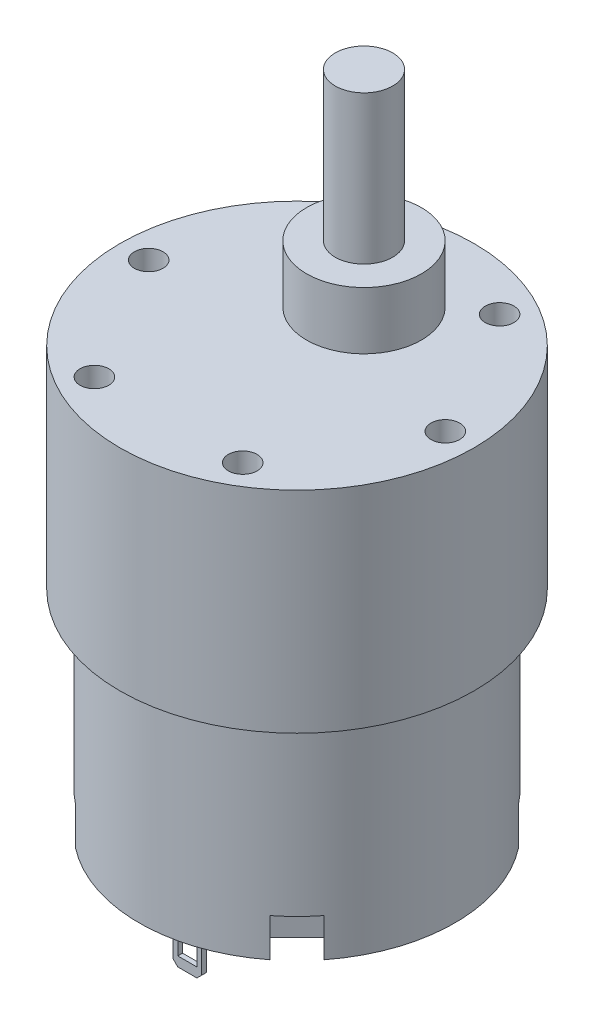
SolidWorks part; units mm, degrees
ref_plane "前视基准面" through (0, 0, 0) normal (0, 0, 1) x (1, 0, 0)
ref_plane "上视基准面" through (0, 0, 0) normal (0, 1, 0) x (1, 0, 0)
ref_plane "右视基准面" through (0, 0, 0) normal (1, 0, 0) x (0, 0, -1)
sketch "草图1" plane through (0, 0, 0) normal (0, 1, 0) x (1, 0, 0)
  circle A0 centre (0, 0) radius 16.5
extrude "凸台-拉伸1" add sketch "草图1" along normal blind 22
sketch "草图2" plane through (0, 22, 0) normal (0, 1, 0) x (1, 0, 0)
  circle A0 centre (0, 0) radius 18.5
extrude "凸台-拉伸2" add sketch "草图2" along normal blind 22
sketch "草图3" plane through (0, 44, 0) normal (0, 1, 0) x (1, 0, 0)
  circle A0 centre (0, 7) radius 6
extrude "凸台-拉伸3" add sketch "草图3" along normal blind 6
sketch "草图4" plane through (0, 50, 0) normal (0, 1, 0) x (1, 0, 0)
  circle A0 centre (0, 7) radius 3
extrude "凸台-拉伸7" add sketch "草图4" along normal blind 15.5
sketch "草图5" plane through (0, 0, 0) normal (0, -1, 0) x (1, 0, 0)
  line L0 (-10.9602, 8.1317) -> (-8.1317, 10.9602)
  line L1 (8.1317, 10.9602) -> (10.9602, 8.1317)
  line L2 (8.1317, 10.9602) -> (10.167, 12.9954)
  line L3 (-10.9602, 8.1317) -> (-12.9954, 10.167)
  line L4 (-8.1317, 10.9602) -> (-10.167, 12.9954)
  line L5 (10.9602, 8.1317) -> (12.9954, 10.167)
  line L6 (10.9602, -8.1317) -> (8.1317, -10.9602)
  line L7 (10.9602, -8.1317) -> (12.9954, -10.167)
  line L8 (8.1317, -10.9602) -> (10.167, -12.9954)
  line L9 (-8.1317, -10.9602) -> (-10.9602, -8.1317)
  line L10 (-8.1317, -10.9602) -> (-10.167, -12.9954)
  line L11 (-10.9602, -8.1317) -> (-12.9954, -10.167)
  arc A2 (-10.167, 12.9954) -> (-12.9954, 10.167) centre (0, 0) ccw
  arc A3 (-12.9954, -10.167) -> (-10.167, -12.9954) centre (0, 0) ccw
  arc A4 (10.167, -12.9954) -> (12.9954, -10.167) centre (0, 0) ccw
  arc A5 (12.9954, 10.167) -> (10.167, 12.9954) centre (0, 0) ccw
  point P26 (0, 0)
  dimension "D1" = 4
extrude "切除-拉伸1" cut sketch "草图5" against normal blind 4
sketch "草图6" plane through (0, 0, 0) normal (0, -1, 0) x (1, 0, 0)
  circle A0 centre (0, 0) radius 4
extrude "凸台-拉伸5" add sketch "草图6" along normal blind 3
sketch "草图7" plane through (0, 44, 0) normal (0, 1, 0) x (1, 0, 0)
  circle A1 centre (15.5, 0) radius 1.5
  circle A2 centre (7.75, -13.4234) radius 1.5
  circle A3 centre (-7.75, -13.4234) radius 1.5
  circle A4 centre (-15.5, 0) radius 1.5
  circle A5 centre (-7.75, 13.4234) radius 1.5
  circle A6 centre (7.75, 13.4234) radius 1.5
  point P16 (0, 0)
extrude "切除-拉伸2" cut sketch "草图7" against normal blind 6
sketch "草图8" plane through (0, 0, 0) normal (0, -1, 0) x (1, 0, 0)
  line L0 (-1.5, 10.9602) -> (1.5, 10.9602)
  line L2 (1.5, 10.9602) -> (1.5, 11.4602)
  line L3 (1.5, 11.4602) -> (-1.5, 11.4602)
  line L4 (-1.5, 11.4602) -> (-1.5, 10.9602)
  line L5 (-1.5, -11.4602) -> (-1.5, -10.9602)
  line L6 (1.5, -11.4602) -> (-1.5, -11.4602)
  line L7 (1.5, -10.9602) -> (1.5, -11.4602)
  line L8 (-1.5, -10.9602) -> (1.5, -10.9602)
extrude "凸台-拉伸6" add sketch "草图8" along normal blind 7
sketch "草图9" plane through (0, 0, 11.4602) normal (0, 0, 1) x (1, 0, 0)
  line L0 (1.5, -7) -> (1, -7)
  line L1 (1.5, -7) -> (-1.5, -7) construction
  line L2 (1.5, -7) -> (1.5, -6.5)
  line L3 (1.5, -7) -> (1.5, 0) construction
  line L4 (1.5, -6.5) -> (1, -7)
  line L5 (-1.5, -7) -> (-1, -7)
  line L6 (-1.5, -7) -> (-1.5, -6.5)
  line L7 (-1.5, -7) -> (-1.5, 0) construction
  line L8 (-1.5, -6.5) -> (-1, -7)
  line L10 (1, -6) -> (1, -3)
  line L11 (1, -3) -> (-1, -3)
  line L12 (-4, -3) -> (4, -3) construction
  line L13 (-1, -3) -> (-1, -6)
  line L14 (-1, -6) -> (1, -6)
extrude "切除-拉伸3" cut sketch "草图9" against normal blind 1
sketch "草图10" plane through (0, 0, -11.4602) normal (0, 0, -1) x (-1, 0, 0)
  line L0 (1.5, -7) -> (1, -7)
  line L1 (1.5, -7) -> (1.5, -6.5)
  line L2 (1.5, -6.5) -> (1, -7)
  line L3 (-1.5, -7) -> (-1, -7)
  line L4 (-1.5, -7) -> (-1.5, -6.5)
  line L5 (-1.5, -6.5) -> (-1, -7)
  line L6 (1, -6) -> (1, -3)
  line L7 (1, -3) -> (-1, -3)
  line L8 (-1, -3) -> (-1, -6)
  line L9 (-1, -6) -> (1, -6)
extrude "切除-拉伸4" cut sketch "草图10" against normal blind 1
move or copy body "实体-移动/复制1" [suppressed] bodies to move or copy 115
